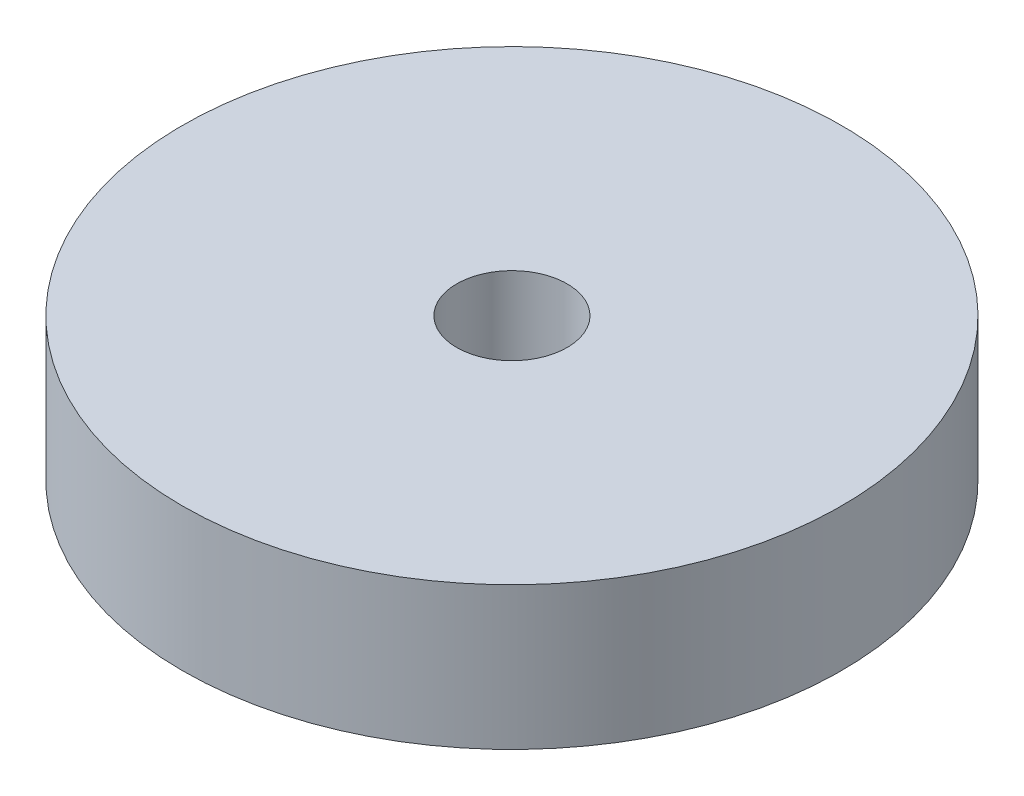
SolidWorks part; units mm, degrees
material "Balsa"
ref_plane "Front Plane" through (0, 0, 0) normal (0, 0, 1) x (1, 0, 0)
ref_plane "Top Plane" through (0, 0, 0) normal (0, 1, 0) x (1, 0, 0)
ref_plane "Right Plane" through (0, 0, 0) normal (1, 0, 0) x (0, 0, -1)
sketch "Sketch1" plane through (0, 0, 0) normal (0, 0, 1) x (1, 0, 0)
  line L3 (14.6685, 0) -> (14.6685, 6.35)
  line L4 (14.6685, 6.35) -> (0, 6.35)
  line L6 (0, 93.7602) -> (0, -51.178) construction
  line L7 (14.6685, 0) -> (0, 0)
  line L8 (0, 0) -> (0, 6.35)
  dimension "D1" = 29.337
  dimension "D2" = 6.35
revolve "Revolve1" add sketch "Sketch1" angle 360 about L6
hole_wizard "#10 (0.1935) Diameter Hole1" positions "Sketch2" profile "Sketch4" hole size "#10" standard "ANSI Inch" end condition through all
sketch "Sketch2" plane through (0, 6.35, 0) normal (0, 1, 0) x (1, 0, 0)
  point P0 (0, 0)
sketch "Sketch4" plane through (0, 6.35, 0) normal (1, 0, 0) x (0, 0, 1)
  line L0 (0, 0) -> (0, 6.35)
  line L1 (0, 6.35) -> (2.4574, 6.35)
  line L2 (2.4574, 6.35) -> (2.4574, 0)
  line L5 (2.4574, 0) -> (0, 0)
  line L11 (0, -6.35) -> (0, 107.95) construction
  dimension "Thru Hole Dia." = 4.9149
  dimension "Thru Hole Depth" = 6.35
